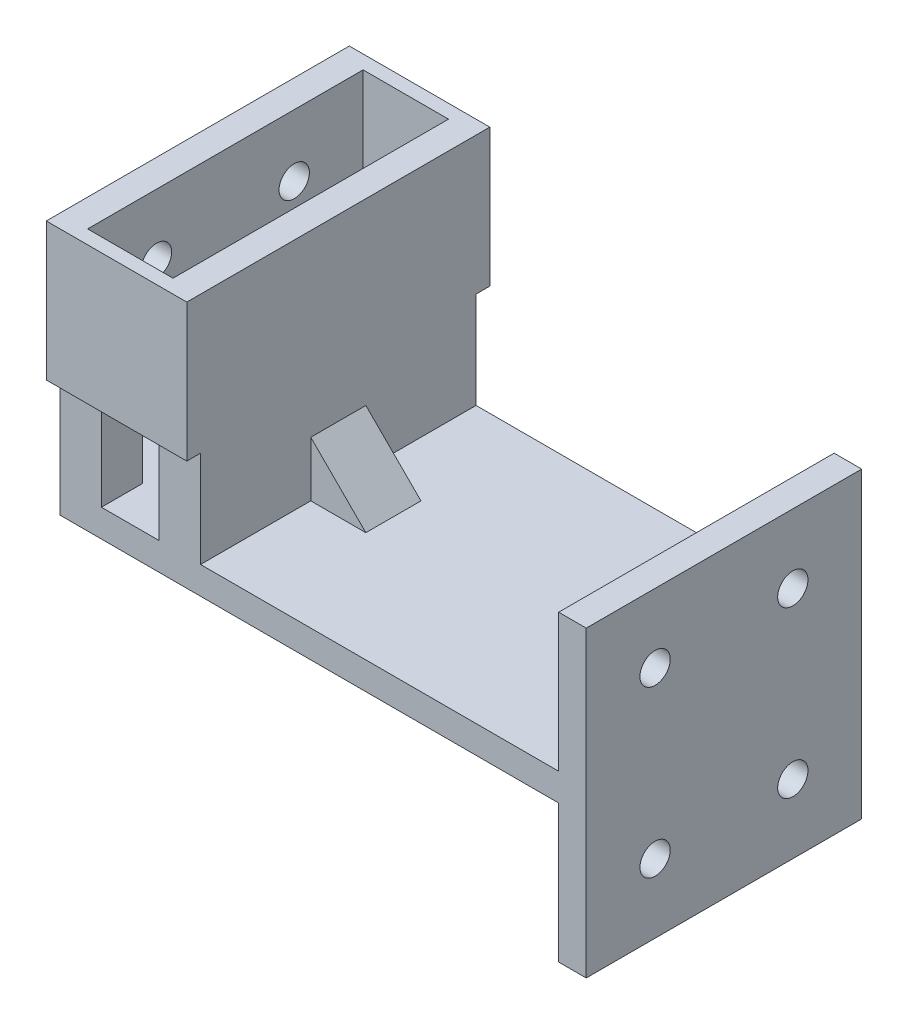
SolidWorks part; units mm, degrees
material "ABS"
ref_plane "Front Plane" through (0, 0, 0) normal (0, 0, 1) x (1, 0, 0)
ref_plane "Top Plane" through (0, 0, 0) normal (0, 1, 0) x (1, 0, 0)
ref_plane "Right Plane" through (0, 0, 0) normal (1, 0, 0) x (0, 0, -1)
sketch "Sketch1" plane through (0, 0, 0) normal (0, 0, 1) x (1, 0, 0)
  line L0 (0, 11) -> (0, -8)
  line L1 (0, 11) -> (2, 11)
  line L2 (2, 11) -> (2, 2)
  line L3 (2, 2) -> (3, 2)
  line L4 (8.2, 2) -> (8.2, 11)
  line L5 (8.2, 11) -> (10.2, 11)
  line L6 (8.2, -8) -> (38.2, -8)
  line L7 (38.2, -8) -> (38.2, -6)
  line L8 (3, 2) -> (3, -6)
  line L9 (3, -6) -> (7.2, -6)
  line L10 (7.2, -6) -> (7.2, 2)
  line L11 (7.2, 2) -> (8.2, 2)
  line L12 (36.2, -6) -> (10.2, -6)
  line L13 (10.2, -6) -> (10.2, 11)
  line L14 (38.2, -6) -> (38.2, 4)
  line L15 (38.2, 4) -> (36.2, 4)
  line L16 (0, -8) -> (8.2, -8)
  line L17 (36.2, 4) -> (36.2, -6)
  dimension "D1" = 2
  dimension "D2" = 9
  dimension "D3" = 8
  dimension "D4" = 2
  dimension "D5" = 2
  dimension "D6" = 28
  dimension "D7" = 6.2
  dimension "D8" = 2
  dimension "D9" = 10
extrude "Boss-Extrude1" add sketch "Sketch1" along normal mid plane 20
sketch "Sketch2" plane through (0, 0, 0) normal (-1, 0, 0) x (0, 0, 1)
  line L0 (10, -8) -> (-10, -8) construction
  line L1 (-7, -6) -> (7, -6)
  line L2 (-7, -6) -> (-7, -2)
  line L3 (-7, -2) -> (7, -2)
  line L4 (7, -6) -> (7, -2)
  line L5 (-10, 11) -> (-10, -8) construction
  line L6 (10, 11) -> (10, -8) construction
  dimension "D1" = 2
  dimension "D2" = 3
  dimension "D3" = 3
  dimension "D4" = 4
extrude "Cut-Extrude1" cut sketch "Sketch2" against normal up to surface (3 mm away) up to face at (3, -2, 0)
sketch "Sketch13" plane through (0, 0, 0) normal (-1, 0, 0) x (0, 0, 1)
  line L0 (-1.7465, 6.5) -> (22.5483, 6.5) construction
  line L1 (10, 11) -> (-10, 11) construction
  line L2 (-10, 11) -> (-10, -8) construction
  line L3 (10, 11) -> (10, -8) construction
  circle A0 centre (-5, 6.5) radius 1.1
  circle A1 centre (5, 6.5) radius 1.1
  dimension "D2" = 2.2
  dimension "D3" = 2.2
  dimension "D1" = 4.5
  dimension "D4" = 5
  dimension "D5" = 5
extrude "Cut-Extrude4" cut sketch "Sketch13" against normal blind 5
sketch "Sketch14" plane through (0, -8, 0) normal (0, -1, 0) x (1, 0, 0)
  line L0 (38.2, 10) -> (38.2, -10)
  line L1 (38.2, -10) -> (36.2, -10)
  line L2 (0, -10) -> (38.2, -10) construction
  line L3 (36.2, -10) -> (36.2, 10)
  line L4 (0, 10) -> (38.2, 10) construction
  line L5 (36.2, 10) -> (38.2, 10)
  dimension "D1" = 2
extrude "Boss-Extrude2" add sketch "Sketch14" along normal blind 10
sketch "Sketch15" plane through (0, 0, 0) normal (0, 0, 1) x (1, 0, 0)
  line L0 (14.2, -6) -> (10.2, -6)
  line L1 (36.2, -6) -> (10.2, -6) construction
  line L2 (10.2, -6) -> (10.2, -2)
  line L3 (10.2, -6) -> (10.2, 11) construction
  line L4 (10.2, -2) -> (14.2, -6)
  line L5 (36.2, -6) -> (36.2, -2)
  line L6 (36.2, 4) -> (36.2, -6) construction
  line L7 (36.2, -2) -> (32.2, -6)
  line L8 (32.2, -6) -> (36.2, -6)
  line L9 (36.2, -8) -> (32.2, -8)
  line L10 (0, -8) -> (36.2, -8) construction
  line L11 (32.2, -8) -> (36.2, -12)
  line L12 (36.2, -18) -> (36.2, -8) construction
  line L13 (36.2, -12) -> (36.2, -8)
  dimension "D1" = 4
  dimension "D2" = 4
  dimension "D3" = 4
  dimension "D4" = 4
  dimension "D5" = 4
  dimension "D6" = 4
extrude "Boss-Extrude3" add sketch "Sketch15" along normal mid plane 4
sketch "Sketch17" plane through (38.2, 0, 0) normal (1, 0, 0) x (0, 0, -1)
  line L0 (-12.2993, -1) -> (16.4603, -1) construction
  line L1 (-12.2993, -13) -> (16.4603, -13) construction
  line L2 (10, -18) -> (-10, -18) construction
  line L3 (-10, 4) -> (10, 4) construction
  line L5 (-10, -18) -> (-10, 4) construction
  line L7 (10, -18) -> (10, 4) construction
  circle A0 centre (-5, -1) radius 1.1
  circle A1 centre (5, -1) radius 1.1
  circle A2 centre (-5, -13) radius 1.1
  circle A3 centre (5, -13) radius 1.1
  dimension "D3" = 2.2
  dimension "D1" = 5
  dimension "D2" = 5
  dimension "D4" = 5
  dimension "D5" = 5
  dimension "D6" = 5
  dimension "D7" = 5
extrude "Cut-Extrude5" cut sketch "Sketch17" against normal blind 4
sketch "Sketch18" plane through (0, 11, 0) normal (0, 1, 0) x (1, 0, 0)
  line L0 (0, -10) -> (10.2, -10)
  line L1 (10.2, -10) -> (10.2, -11)
  line L2 (10.2, -11) -> (0, -11)
  line L3 (0, -11) -> (0, -10)
  line L4 (0, 10) -> (10.2, 10)
  line L5 (10.2, 10) -> (10.2, 11)
  line L6 (10.2, 11) -> (0, 11)
  line L7 (0, 11) -> (0, 10)
  dimension "D1" = 1
  dimension "D2" = 1
extrude "Boss-Extrude4" add sketch "Sketch18" against normal blind 10
